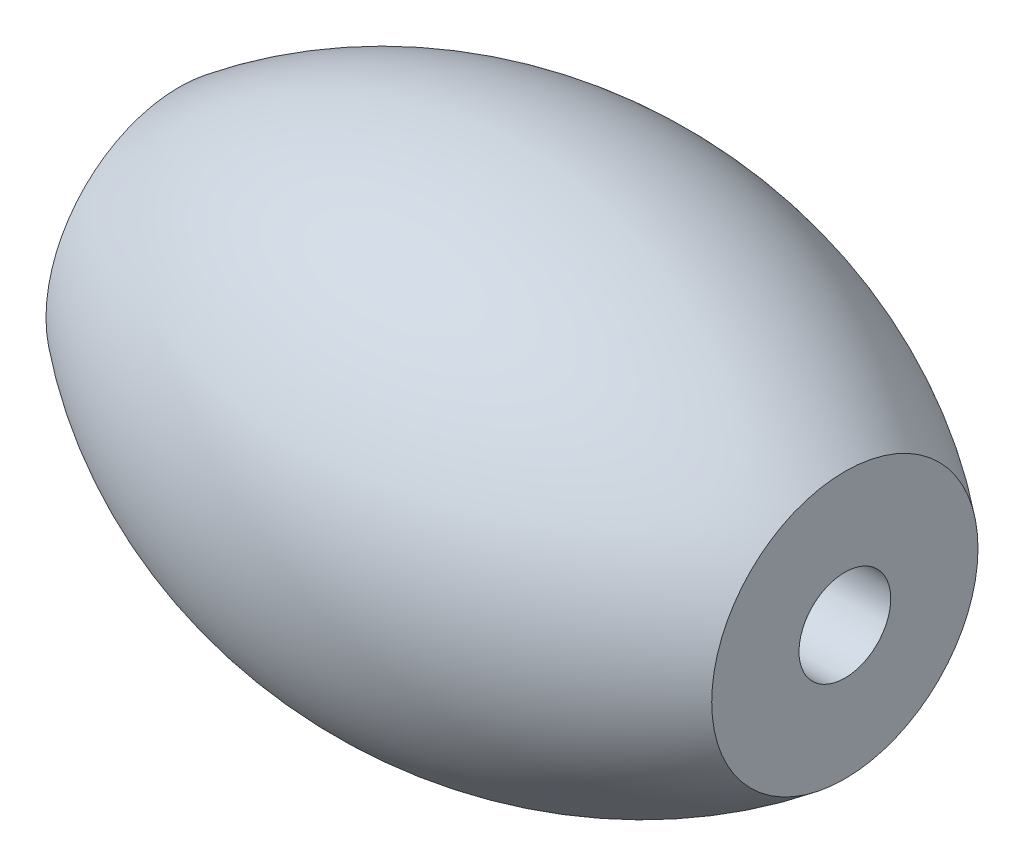
SolidWorks part; units mm, degrees
ref_plane "Front Plane" through (0, 0, 0) normal (0, 0, 1) x (1, 0, 0)
ref_plane "Top Plane" through (0, 0, 0) normal (0, 1, 0) x (1, 0, 0)
ref_plane "Right Plane" through (0, 0, 0) normal (1, 0, 0) x (0, 0, -1)
sketch "Sketch1" plane through (0, 0, 0) normal (0, 0, 1) x (1, 0, 0)
  line L0 (0, 0) -> (25.4, 0)
  line L3 (0, 1.75) -> (25.4, 1.75)
  line L4 (0, 5.08) -> (0, 1.75)
  line L5 (0, 0) -> (0, 1.75)
  line L6 (25.4, 5.08) -> (25.4, 1.75)
  line L7 (25.4, 0) -> (25.4, 1.75)
  arc A0 (0, 5.08) -> (25.4, 5.08) centre (12.7, -11.0952) cw
  arc A1 (0, 5.08) -> (25.4, 5.08) centre (12.7, -13.9276) cw construction
  point P6 (25.4, 0)
  point P8 (12.7, 9.47)
  point P9 (0, 0)
  point P11 (12.7, 0)
  dimension "D5" = 22.86
  dimension "D1" = 1.75
  dimension "D2" = 9.47
  dimension "D3" = 25.4
  dimension "D4" = 5.08
revolve "Revolve1" add sketch "Sketch1" angle 360 about L0
